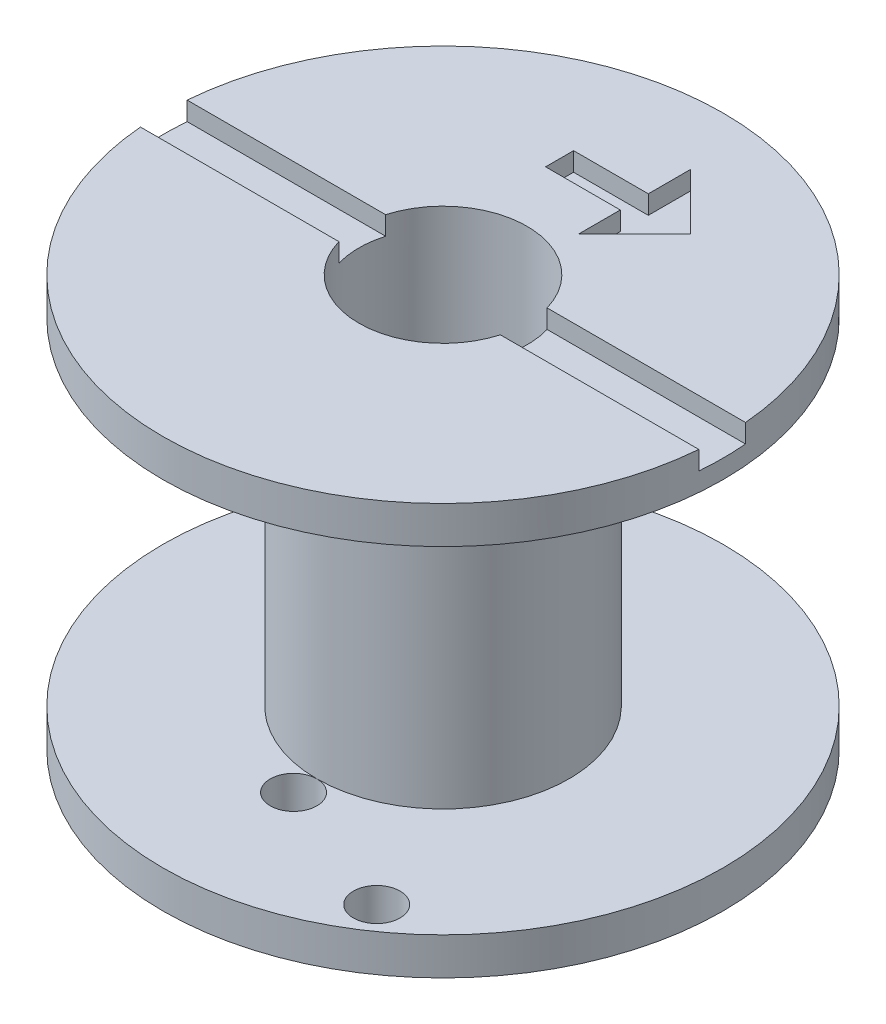
SolidWorks part; units mm, degrees
ref_plane "Front Plane" through (0, 0, 0) normal (0, 0, 1) x (1, 0, 0)
ref_plane "Top Plane" through (0, 0, 0) normal (0, 1, 0) x (1, 0, 0)
ref_plane "Right Plane" through (0, 0, 0) normal (1, 0, 0) x (0, 0, -1)
sketch "Sketch2" plane through (0, 0, 0) normal (1, 0, 0) x (0, 0, -1)
  line L0 (0, 15.5) -> (0, -9.6242) construction
  line L1 (-15, 11) -> (-15, 9)
  line L2 (-15, 9) -> (-6.75, 9)
  line L3 (-6.75, 9) -> (-6.75, -9)
  line L4 (0, 0) -> (-6.75, 0) construction
  line L5 (-15, 11) -> (-4.5, 11)
  line L6 (-15, -9) -> (-6.75, -9)
  line L7 (-15, -11) -> (-15, -9)
  line L14 (-15, -11) -> (-8.5, -11)
  line L16 (-4.5, 11) -> (-4.5, -12)
  line L17 (-8.5, -11) -> (-8.5, -13)
  line L18 (-8.5, -13) -> (-4.5, -13)
  line L19 (-4.5, -13) -> (-4.5, -12)
  point P13 (0, -15.5)
  dimension "D1" = 2
  dimension "D2" = 13.5
  dimension "D3" = 2
  dimension "D4" = 18
  dimension "D5" = 9
  dimension "D6" = 4
  dimension "D7" = 30
  dimension "D8" = 8.25
  dimension "D9" = 18
  dimension "D10" = 2
revolve "Revolve1" add sketch "Sketch2" angle 360 about L0
sketch "Sketch4" plane through (0, 11, 0) normal (0, 1, 0) x (1, 0, 0)
  line L0 (-2.2583, 9.25) -> (1.7417, 9.25)
  line L1 (1.7417, 9.25) -> (1.7417, 11.5)
  line L2 (1.7417, 11.5) -> (4.7417, 8.5)
  line L3 (4.7417, 8.5) -> (1.7417, 5.5)
  line L4 (1.7417, 5.5) -> (1.7417, 7.75)
  line L5 (1.7417, 7.75) -> (-2.2583, 7.75)
  line L6 (-2.2583, 7.75) -> (-2.2583, 9.25)
  line L7 (-2.2583, 8.5) -> (4.7417, 8.5) construction
  point P8 (-2.2583, 8.5)
  dimension "D1" = 1.5
  dimension "D2" = 4
  dimension "D3" = 4
  dimension "D4" = 6
  dimension "D5" = 3
  dimension "D6" = 8.5
extrude "Cut-Extrude2" cut sketch "Sketch4" against normal blind 1
sketch "Sketch5" plane through (0, -13, 0) normal (0, -1, 0) x (1, 0, 0)
  line L1 (21.3058, -1.25) -> (-21.3058, -1.25)
  line L2 (21.3058, -1.25) -> (21.3058, 1.25)
  line L3 (21.3058, 1.25) -> (-21.3058, 1.25)
  line L4 (-21.3058, -1.25) -> (-21.3058, 1.25)
  line L5 (21.3058, -1.25) -> (-21.3058, 1.25) construction
  line L6 (21.3058, 1.25) -> (-21.3058, -1.25) construction
  point P0 (0, 0)
  dimension "D1" = 2.5
extrude "Cut-Extrude3" cut sketch "Sketch5" along normal blind 17 and the other way blind 1 from offset 40 offset against normal yes
sketch "Sketch3" plane through (0, -11, 0) normal (0, -1, 0) x (1, 0, 0)
  circle A0 centre (0, 8) radius 1.25
  circle A1 centre (7.4254, 10.9739) radius 1.25
  dimension "D3" = 2.5
  dimension "D4" = 2.5
  dimension "D1" = 8
  dimension "D2" = 13.25
extrude "Cut-Extrude1" cut sketch "Sketch3" against normal mid plane 19
